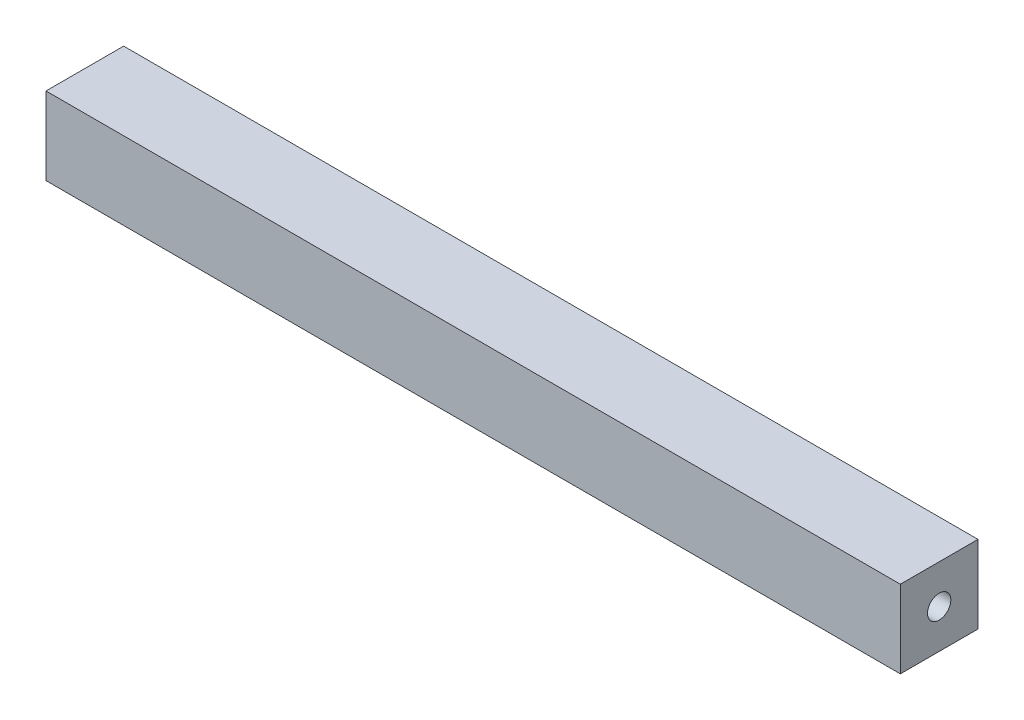
SolidWorks part; units mm, degrees
ref_plane "正面" through (0, 0, 0) normal (0, 0, 1) x (1, 0, 0)
ref_plane "平面" through (0, 0, 0) normal (0, 1, 0) x (1, 0, 0)
ref_plane "右側面" through (0, 0, 0) normal (1, 0, 0) x (0, 0, -1)
sketch "ｽｹｯﾁ1" plane through (0, 0, 0) normal (0, 1, 0) x (1, 0, 0)
  line L1 (-55, -5) -> (55, -5)
  line L2 (-55, -5) -> (-55, 5)
  line L3 (-55, 5) -> (55, 5)
  line L4 (55, -5) -> (55, 5)
  line L5 (-55, -5) -> (55, 5) construction
  line L6 (-55, 5) -> (55, -5) construction
  point P0 (0, 0)
  dimension "D1" = 110
  dimension "D2" = 10
extrude "ﾎﾞｽ - 押し出し1" add sketch "ｽｹｯﾁ1" along normal blind 10
sketch "ｽｹｯﾁ2" plane through (0, 0, 0) normal (1, 0, 0) x (0, 0, -1)
  line L0 (-5, 10) -> (5, 0) construction
  line L1 (-5, 0) -> (5, 10) construction
  circle A0 centre (0, 5) radius 1.5
  point P10 (0, 6.4346)
  point P11 (0, 0)
  point P12 (0, 5)
  dimension "D1" = 3
extrude "ｶｯﾄ - 押し出し1" cut sketch "ｽｹｯﾁ2" against normal through all both and the other way through all
